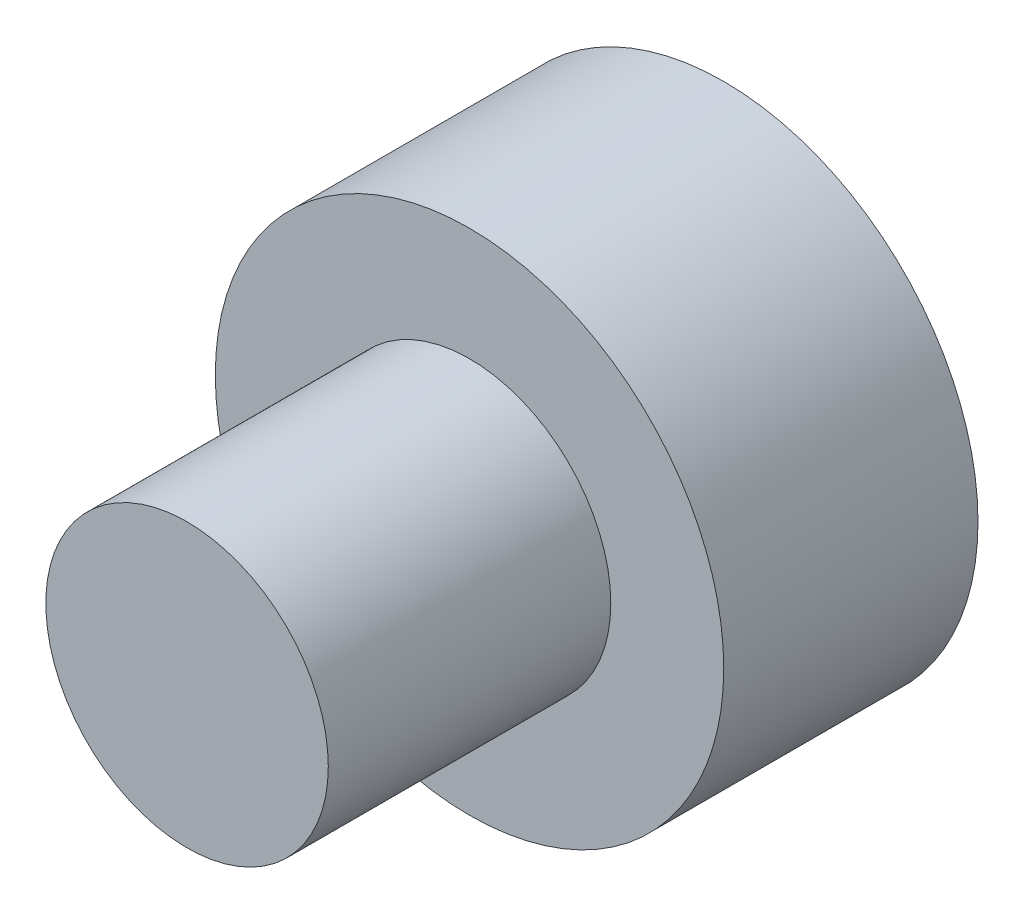
SolidWorks part; units mm, degrees
ref_plane "Front Plane" through (0, 0, 0) normal (0, 0, 1) x (1, 0, 0)
ref_plane "Top Plane" through (0, 0, 0) normal (0, 1, 0) x (1, 0, 0)
ref_plane "Right Plane" through (0, 0, 0) normal (1, 0, 0) x (0, 0, -1)
sketch "Sketch1" plane through (0, 0, 0) normal (0, 0, 1) x (1, 0, 0)
  circle A0 centre (0, 0) radius 4.5
  dimension "D1" = 9
extrude "Boss-Extrude3" add sketch "Sketch1" along normal blind 4.5 contours A0
sketch "Sketch4" plane through (0, 0, 0) normal (0, 0, -1) x (-1, 0, 0)
  line L1 (3.1503, 0.0941) -> (1.4936, 2.7753)
  line L2 (1.4936, 2.7753) -> (-1.6567, 2.6812)
  line L3 (-1.6567, 2.6812) -> (-3.1503, -0.0941)
  line L4 (-3.1503, -0.0941) -> (-1.4936, -2.7753)
  line L5 (-1.4936, -2.7753) -> (1.6567, -2.6812)
  line L6 (1.6567, -2.6812) -> (3.1503, 0.0941)
  circle A0 centre (0, 0) radius 2.7295 construction
extrude "Cut-Extrude2" cut sketch "Sketch4" against normal blind 2
sketch "Sketch5" plane through (0, 0, 4.5) normal (0, 0, 1) x (1, 0, 0)
  circle A0 centre (0, 0) radius 2.5
extrude "Boss-Extrude4" add sketch "Sketch5" along normal blind 5
